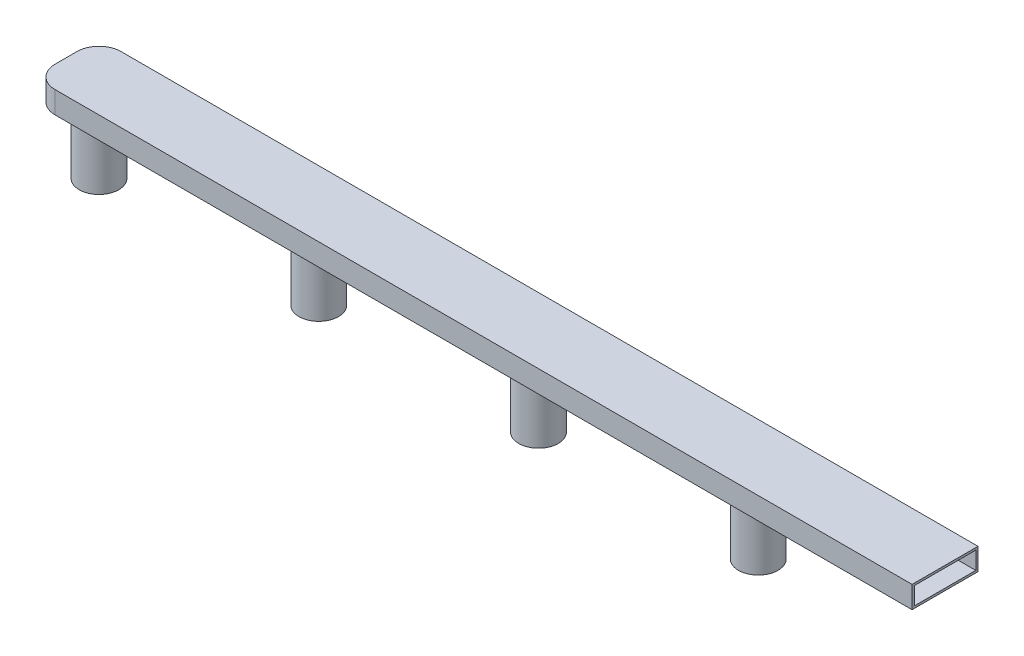
SolidWorks part; units mm, degrees
material "Cast Alloy Steel"
ref_plane "Front Plane" through (0, 0, 0) normal (0, 0, 1) x (1, 0, 0)
ref_plane "Top Plane" through (0, 0, 0) normal (0, 1, 0) x (1, 0, 0)
ref_plane "Right Plane" through (0, 0, 0) normal (1, 0, 0) x (0, 0, -1)
sketch "Sketch1" plane through (0, 0, 0) normal (0, 1, 0) x (1, 0, 0)
  circle A0 centre (-150, 0) radius 6.5
  circle A1 centre (-50, 0) radius 6.5
  circle A2 centre (50, 0) radius 6.5
  circle A3 centre (150, 0) radius 6.5
  circle A4 centre (-150, 0) radius 9
  circle A5 centre (-50, 0) radius 9
  circle A6 centre (50, 0) radius 9
  circle A7 centre (150, 0) radius 9
  dimension "D1" = 13
  dimension "D6" = 18
  dimension "D2" = 50
  dimension "D3" = 100
  dimension "D4" = 100
  dimension "D5" = 50
extrude "Boss-Extrude1" add sketch "Sketch1" against normal blind 30
sketch "Sketch2" plane through (0, 0, 0) normal (0, 1, 0) x (1, 0, 0)
  line L1 (-155, 15) -> (235, 15)
  line L2 (-165, 5) -> (-165, -5)
  line L3 (-155, -15) -> (235, -15)
  line L4 (235, 15) -> (235, -15)
  circle A0 centre (150, 0) radius 9 construction
  circle A1 centre (-150, 0) radius 9 construction
  arc A4 (-165, -5) -> (-155, -15) centre (-155, -5) ccw
  arc A5 (-155, 15) -> (-165, 5) centre (-155, 5) ccw
  point P1 (-165, 0)
  point P4 (235, 0)
  point P12 (235, 15)
  point P15 (235, -15)
  dimension "D2" = 85
  dimension "D3" = 15
  dimension "D4" = 10
  dimension "D1" = 30
extrude "Boss-Extrude2" add sketch "Sketch2" along normal blind 10 separate body
shell "Shell3" thickness 1
